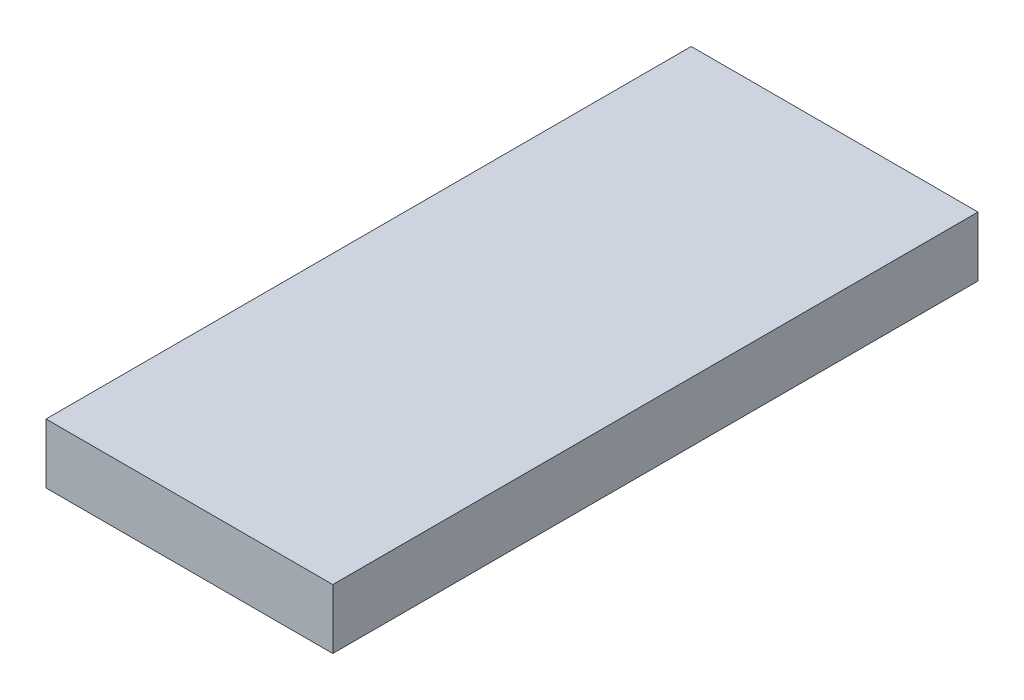
SolidWorks part; units mm, degrees
material "Driver ESC"
ref_plane "Alzado" through (0, 0, 0) normal (0, 0, 1) x (1, 0, 0)
ref_plane "Planta" through (0, 0, 0) normal (0, 1, 0) x (1, 0, 0)
ref_plane "Vista lateral" through (0, 0, 0) normal (1, 0, 0) x (0, 0, -1)
sketch "Croquis1" plane through (0, 0, 0) normal (0, 1, 0) x (1, 0, 0)
  line L1 (12, -27) -> (-12, -27)
  line L2 (12, -27) -> (12, 27)
  line L3 (12, 27) -> (-12, 27)
  line L4 (-12, -27) -> (-12, 27)
  line L5 (12, -27) -> (-12, 27) construction
  line L6 (12, 27) -> (-12, -27) construction
  point P0 (0, 0)
  dimension "D1" = 24
  dimension "D2" = 54
extrude "Saliente-Extruir1" add sketch "Croquis1" along normal blind 5
